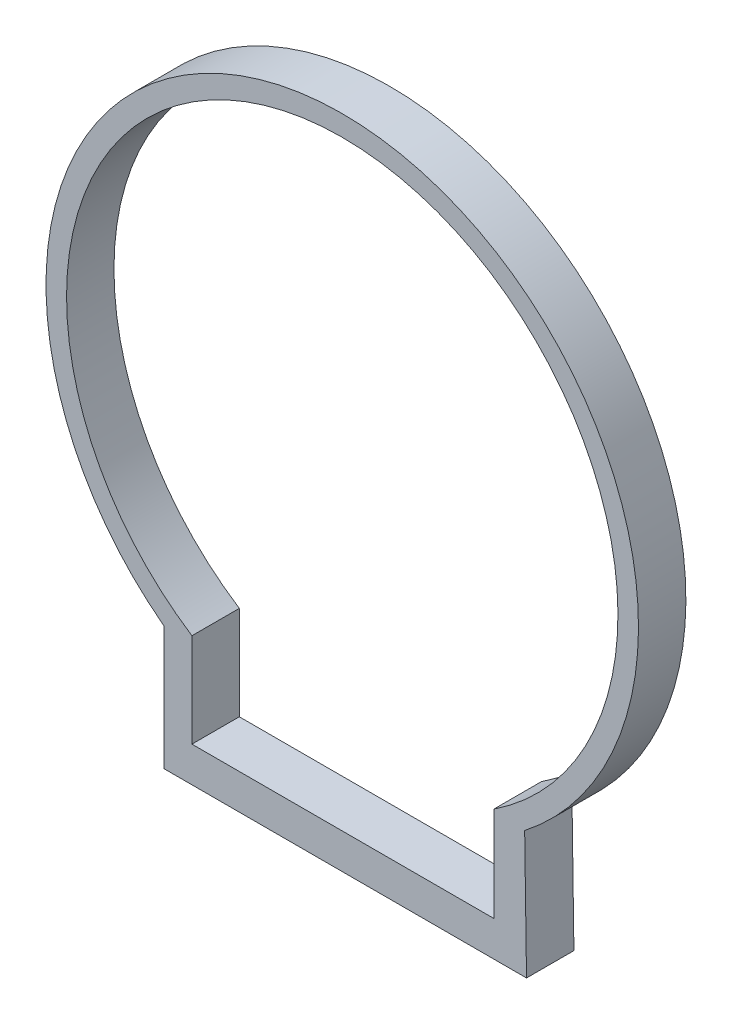
SolidWorks part; units mm, degrees
ref_plane "Front Plane" through (0, 0, 0) normal (0, 0, 1) x (1, 0, 0)
ref_plane "Top Plane" through (0, 0, 0) normal (0, 1, 0) x (1, 0, 0)
ref_plane "Right Plane" through (0, 0, 0) normal (1, 0, 0) x (0, 0, -1)
sketch "Sketch4" plane through (0, 0, 0) normal (0, 0, 1) x (1, 0, 0)
  line L0 (0.1878, -22.8) -> (-11.2872, -22.8)
  line L4 (11.6628, -22.8) -> (0.1878, -22.8)
  line L7 (-11.2872, -14.972) -> (-11.2872, -22.8)
  line L9 (11.6628, -22.8) -> (11.5453, -14.7739)
  arc A1 (-11.2872, -14.972) -> (11.5453, -14.7739) centre (0, 0) cw
  dimension "D1" = 18.75
  dimension "D2" = 11.475
  dimension "D3" = 22.8
extrude "Boss-Extrude1" add sketch "Sketch4" along normal blind 3
sketch "Sketch5" plane through (0, 0, 0) normal (0, 0, 1) x (1, 0, 0)
  line L0 (9.5937, -14.5761) -> (9.5937, -20.5703)
  line L1 (9.5937, -20.5703) -> (-9.5148, -20.5703)
  line L2 (-9.5148, -20.5703) -> (-9.5148, -14.6277)
  arc A0 (-9.5148, -14.6277) -> (9.5937, -14.5761) centre (0, 0) cw
  dimension "D1" = 17.45
extrude "Cut-Extrude1" cut sketch "Sketch5" along normal blind 3
